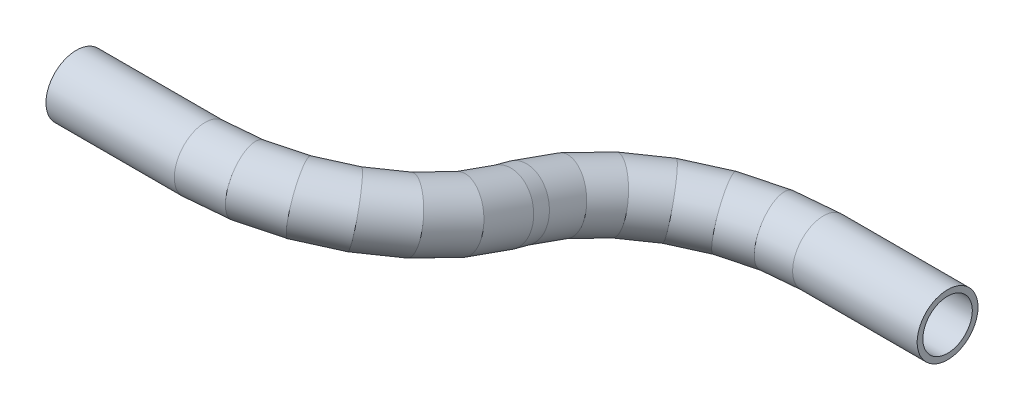
SolidWorks part; units mm, degrees
ref_plane "Front Plane" through (0, 0, 0) normal (0, 0, 1) x (1, 0, 0)
ref_plane "Top Plane" through (0, 0, 0) normal (0, 1, 0) x (1, 0, 0)
ref_plane "Right Plane" through (0, 0, 0) normal (1, 0, 0) x (0, 0, -1)
sketch3d "Path"
  line L0 (-2318.388, -9.3175, -34.7733) -> (-2298.588, -9.3175, -34.7733)
  line L1 (-2298.588, -9.3175, -34.7733) -> (-2292.3763, -9.5291, -35.5632)
  line L2 (-2292.3763, -9.5291, -35.5632) -> (-2286.588, -10.1497, -37.8792)
  line L3 (-2286.588, -10.1497, -37.8792) -> (-2281.6174, -11.1368, -41.5632)
  line L4 (-2281.6174, -11.1368, -41.5632) -> (-2277.8034, -12.4233, -46.3644)
  line L5 (-2277.8034, -12.4233, -46.3644) -> (-2275.4057, -13.9214, -51.9555)
  line L6 (-2275.4057, -13.9214, -51.9555) -> (-2274.588, -15.5291, -57.9555)
  line L7 (-2274.588, -15.5291, -57.9555) -> (-2274.588, -16.1891, -60.4187)
  line L8 (-2274.588, -16.1891, -60.4187) -> (-2273.7702, -17.7968, -66.4187)
  line L9 (-2273.7702, -17.7968, -66.4187) -> (-2271.3726, -19.295, -72.0098)
  line L10 (-2271.3726, -19.295, -72.0098) -> (-2267.5585, -20.5814, -76.811)
  line L11 (-2267.5585, -20.5814, -76.811) -> (-2262.588, -21.5686, -80.4951)
  line L12 (-2262.588, -21.5686, -80.4951) -> (-2256.7996, -22.1891, -82.811)
  line L13 (-2256.7996, -22.1891, -82.811) -> (-2250.588, -22.4008, -83.6009)
  line L14 (-2250.588, -22.4008, -83.6009) -> (-2230.788, -22.4008, -83.6009)
ref_plane "Start Plane" through (-2318.388, 0, 0) normal (1, 0, 0) x (0, 0, -1)
sketch "Profile" plane through (-2318.388, 0, 0) normal (1, 0, 0) x (0, 0, -1)
  circle A0 centre (34.7733, -9.3175) radius 4.7625
  circle A1 centre (34.7733, -9.3175) radius 3.8735
sweep "Tube" add profiles "Profile" path "Path"
